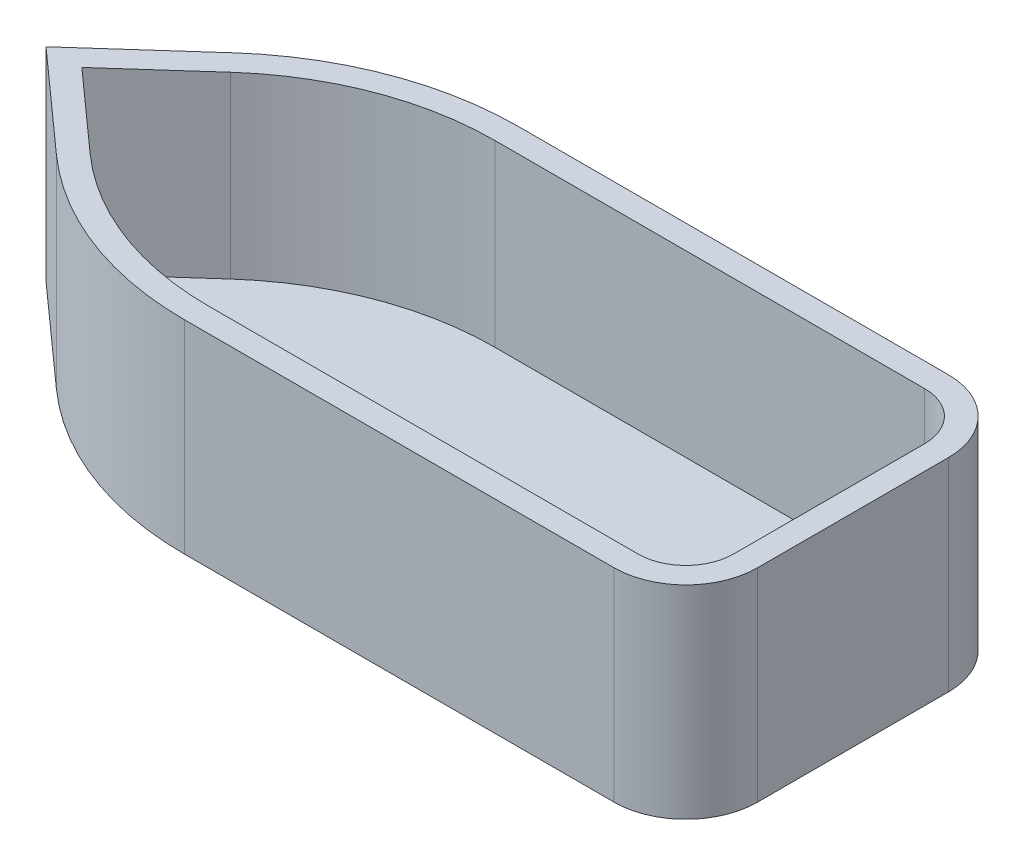
SolidWorks part; units mm, degrees
ref_plane "Front Plane" through (0, 0, 0) normal (0, 0, 1) x (1, 0, 0)
ref_plane "Top Plane" through (0, 0, 0) normal (0, 1, 0) x (1, 0, 0)
ref_plane "Right Plane" through (0, 0, 0) normal (1, 0, 0) x (0, 0, -1)
sketch "Sketch1" plane through (0, 0, 0) normal (0, 1, 0) x (1, 0, 0)
  line L1 (-317.8038, 29.4427) -> (-350.7218, 0)
  line L4 (-237.8038, 60) -> (-57.8038, 60)
  line L5 (-37.8038, -40) -> (-37.8038, 40)
  line L7 (-237.8038, -60) -> (-57.8038, -60)
  line L8 (-317.8038, -29.4427) -> (-350.7218, 0)
  arc A0 (-317.8038, 29.4427) -> (-237.8038, 60) centre (-237.8038, -60) cw
  arc A1 (-237.8038, -60) -> (-317.8038, -29.4427) centre (-237.8038, 60) cw
  arc A2 (-57.8038, 60) -> (-37.8038, 40) centre (-57.8038, 40) cw
  arc A3 (-57.8038, -60) -> (-37.8038, -40) centre (-57.8038, -40) ccw
  point P10 (-283.6397, 60)
  point P13 (-283.6397, -60)
  point P14 (-37.8038, 60)
  point P17 (-37.8038, -60)
  dimension "D4" = 120
  dimension "D5" = 120
  dimension "D6" = 20
  dimension "D7" = 20
  dimension "D1" = 120
  dimension "D2" = 200
  dimension "D3" = 90
extrude "Boss-Extrude1" add sketch "Sketch1" along normal blind 75
shell "Shell1" thickness 10
